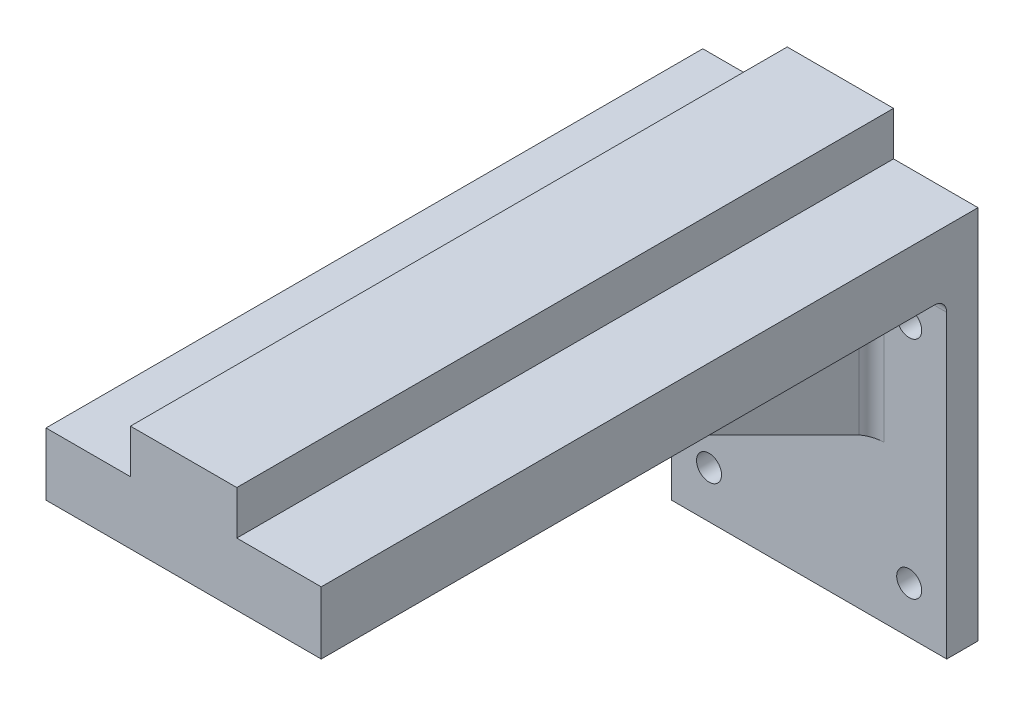
SolidWorks part; units mm, degrees
ref_plane "Front Plane" through (0, 0, 0) normal (0, 0, 1) x (1, 0, 0)
ref_plane "Top Plane" through (0, 0, 0) normal (0, 1, 0) x (1, 0, 0)
ref_plane "Right Plane" through (0, 0, 0) normal (1, 0, 0) x (0, 0, -1)
sketch "Sketch1" plane through (0, 0, 0) normal (0, 0, 1) x (1, 0, 0)
  line L0 (0, 0) -> (-22, 0)
  line L1 (-22, 0) -> (-22, 60)
  line L2 (-22, 60) -> (22, 60)
  line L3 (22, 60) -> (22, 0)
  line L4 (22, 0) -> (0, 0)
extrude "Boss-Extrude1" add sketch "Sketch1" along normal blind 5
sketch "Sketch2" plane through (0, 0, 0) normal (0, 0, -1) x (-1, 0, 0)
  circle A0 centre (-16, 43.5) radius 2
  circle A1 centre (16, 43.5) radius 2
  circle A2 centre (-16, 7.5) radius 2
  circle A3 centre (16, 7.5) radius 2
extrude "Cut-Extrude1" cut sketch "Sketch2" against normal blind 5
sketch "Sketch3" plane through (0, 0, 5) normal (0, 0, 1) x (1, 0, 0)
  line L0 (-22, 60) -> (-22, 50)
  line L1 (-22, 60) -> (-22, 0) construction
  line L2 (-22, 50) -> (22, 50)
  line L3 (22, 0) -> (22, 60) construction
  line L4 (22, 50) -> (22, 60)
  line L5 (22, 60) -> (-22, 60)
extrude "Boss-Extrude2" add sketch "Sketch3" along normal blind 100
sketch "Sketch4" plane through (0, 0, 0) normal (1, 0, 0) x (0, 0, -1)
  line L0 (-5, 50) -> (-5, 25)
  line L1 (-5, 0) -> (-5, 50) construction
  line L2 (-5, 50) -> (-55, 50)
  line L3 (-105, 50) -> (-5, 50) construction
  line L4 (-55, 50) -> (-5, 25)
extrude "Boss-Extrude3" add sketch "Sketch4" along normal mid plane 20
fillet "Fillet1" radius 2 6 edges at (10, 37.5, 5) (10, 50, 30) (-10, 37.5, 5) (-10, 50, 30)
sketch "Sketch5" plane through (0, 60, 0) normal (0, 1, 0) x (1, 0, 0)
  line L1 (22, 0) -> (-22, 0) construction
  line L2 (-8.5, 0) -> (8.5, 0)
  line L3 (8.5, 0) -> (8.5, -105)
  line L4 (22, -105) -> (-22, -105) construction
  line L5 (8.5, -105) -> (-8.5, -105)
  line L6 (-8.5, -105) -> (-8.5, 0)
extrude "Boss-Extrude4" add sketch "Sketch5" along normal blind 7
